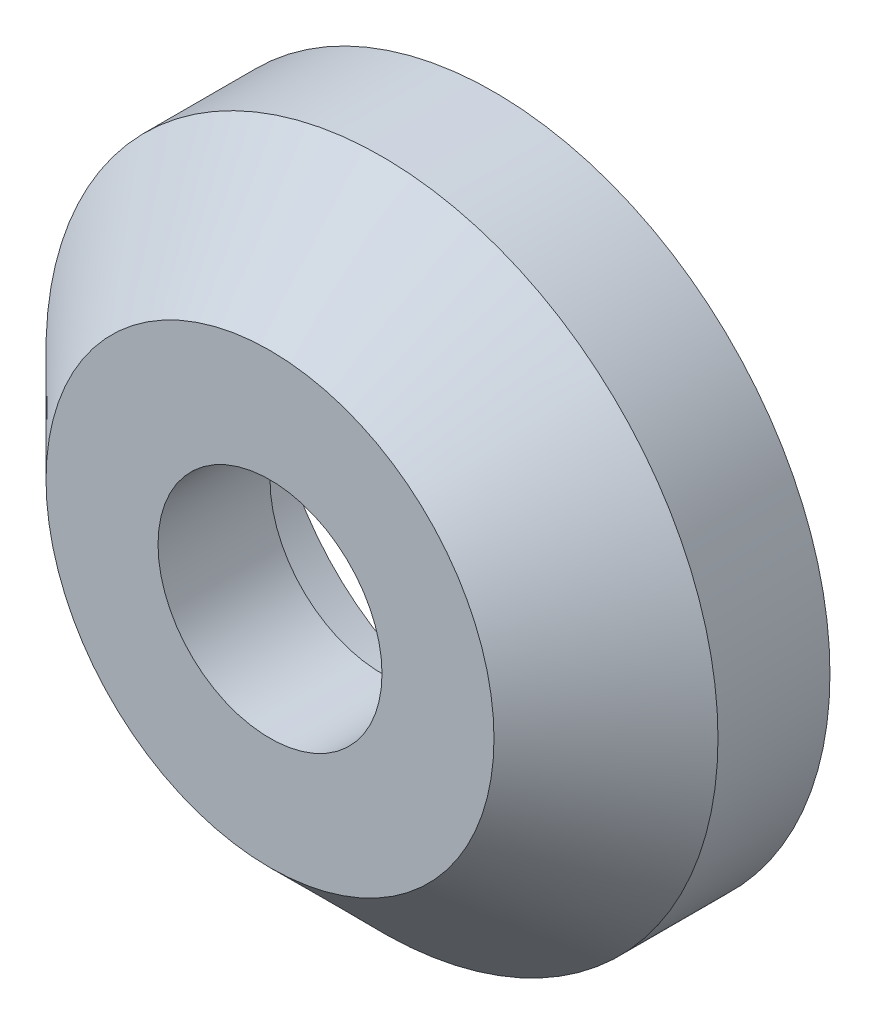
SolidWorks part; units mm, degrees
ref_plane "前视基准面" through (0, 0, 0) normal (0, 0, 1) x (1, 0, 0)
ref_plane "上视基准面" through (0, 0, 0) normal (0, 1, 0) x (1, 0, 0)
ref_plane "右视基准面" through (0, 0, 0) normal (1, 0, 0) x (0, 0, -1)
other "Configuration Table"
sketch "Sketch1" plane through (0, 0, 0) normal (0, 0, 1) x (1, 0, 0)
  circle A0 centre (0, 0) radius 7.5
  circle A1 centre (0, 0) radius 2.5
  dimension "D1" = 15
  dimension "D2" = 5
extrude "Boss-Extrude1" add sketch "Sketch1" along normal blind 5
chamfer "Chamfer1" distance 2.5 angle 45 1 edges at (7.5, 0, 5)
sketch "Sketch2" plane through (0, 0, 0) normal (0, 0, -1) x (-1, 0, 0)
  circle A0 centre (0, 0) radius 5
  dimension "D1" = 10
extrude "Cut-Extrude1" cut sketch "Sketch2" against normal blind 2.5
